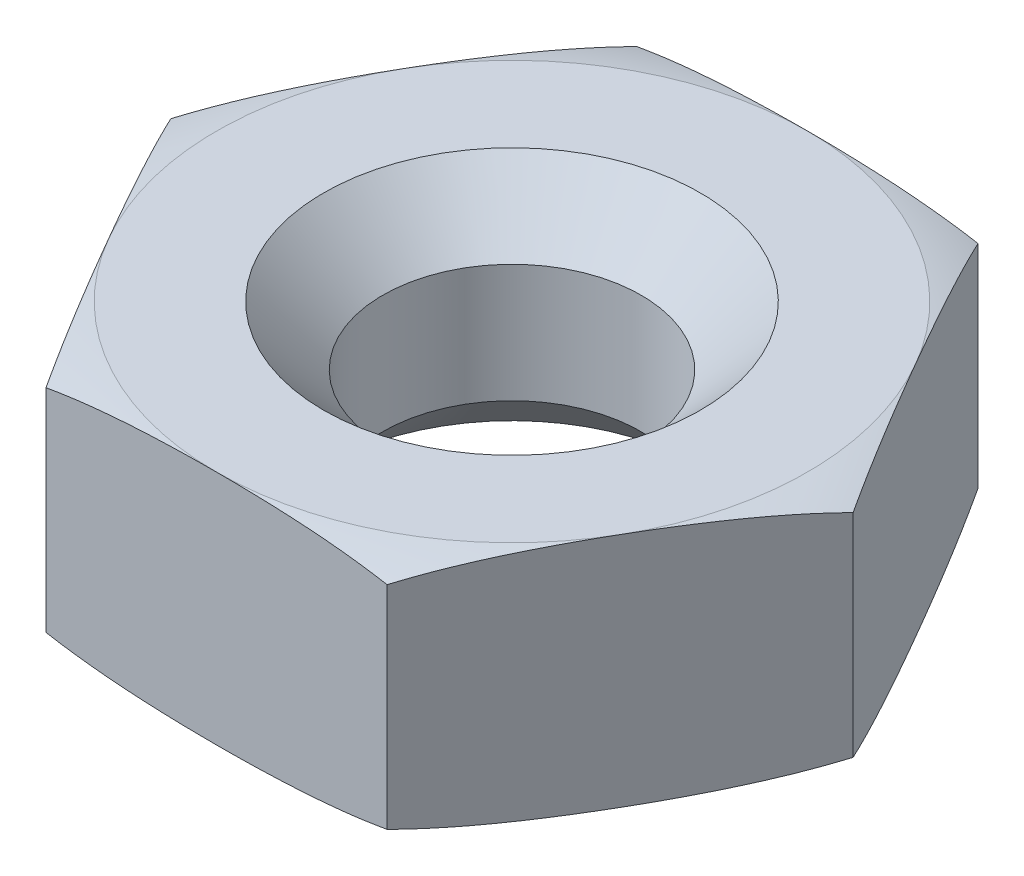
SolidWorks part; units mm, degrees
ref_plane "Front Plane" through (0, 0, 0) normal (0, 0, 1) x (1, 0, 0)
ref_plane "Top Plane" through (0, 0, 0) normal (0, 1, 0) x (1, 0, 0)
ref_plane "Right Plane" through (0, 0, 0) normal (1, 0, 0) x (0, 0, -1)
sketch "Sketch1" plane through (0, 0, 0) normal (0, 1, 0) x (1, 0, 0)
  line L1 (2.3094, 0) -> (1.1547, 2)
  line L2 (1.1547, 2) -> (-1.1547, 2)
  line L3 (-1.1547, 2) -> (-2.3094, 0)
  line L4 (-2.3094, 0) -> (-1.1547, -2)
  line L5 (-1.1547, -2) -> (1.1547, -2)
  line L6 (1.1547, -2) -> (2.3094, 0)
  circle A0 centre (0, 0) radius 2 construction
  circle A1 centre (0, 0) radius 0.875
  dimension "D1" = 1.75
  dimension "D2" = 4
extrude "Boss-Extrude1" add sketch "Sketch1" along normal mid plane 1.6
sketch "Sketch2" plane through (0, 0, 0) normal (1, 0, 0) x (0, 0, -1)
  line L0 (-2, 0.8) -> (-3, 0.8)
  line L1 (-3, 0.8) -> (-3, 0.3)
  line L2 (0, 0.8) -> (0, -0.8) construction
  line L3 (-0.875, 0.8) -> (-0.875, 0.4)
  line L4 (-2, 0.8) -> (0, 0.8) construction
  line L5 (-0.875, 0.4) -> (-1.275, 0.8)
  line L6 (-1.275, 0.8) -> (-0.875, 0.8)
  arc A1 (-3, 0.3) -> (-2, 0.8) centre (-1.6412, -1.1676) cw
  dimension "D1" = 1
  dimension "D3" = 2
  dimension "D2" = 0.5
  dimension "D4" = 0.4
revolve "Cut-Revolve1" cut sketch "Sketch2" angle 360 about L2
mirror "Mirror1" about plane through (0, 0, 0) normal (0, 1, 0) of "Cut-Revolve1"
